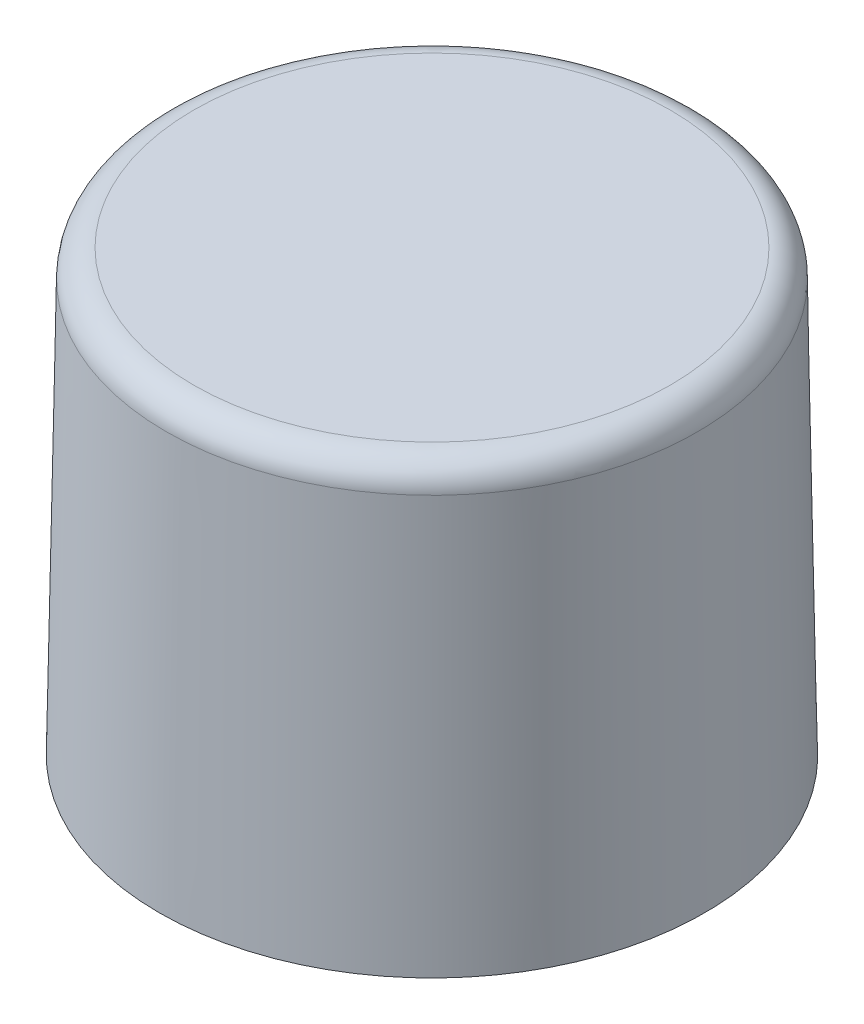
SolidWorks part; units mm, degrees
ref_plane "Front Plane" through (0, 0, 0) normal (0, 0, 1) x (1, 0, 0)
ref_plane "Top Plane" through (0, 0, 0) normal (0, 1, 0) x (1, 0, 0)
ref_plane "Right Plane" through (0, 0, 0) normal (1, 0, 0) x (0, 0, -1)
sketch "Sketch1" plane through (0, 0, 0) normal (0, 0, 1) x (1, 0, 0)
  line L0 (0, 0) -> (0, 4.03)
  line L1 (0, 4.03) -> (-2.4297, 4.03)
  line L2 (-2.4297, 4.03) -> (-2.5, 0)
  line L3 (-2.5, 0) -> (0, 0)
  line L4 (0, 0) -> (0, -1) construction
  line L5 (0, 2.6) -> (-1.8426, 2.6) construction
  line L6 (-2, 0) -> (-1.8845, 0.2)
  line L7 (-1.8845, 0.2) -> (-1.8278, 3.45)
  line L8 (-1.8278, 3.45) -> (0, 3.45)
  point P10 (0, 2.015)
  point P13 (0, -1.0864)
  point P14 (0, 0)
  point P15 (-2, 2.6)
  point P16 (-1.8426, 2.6)
  point P17 (0, 0)
  point P18 (0, 0)
  dimension "D1" = 89
  dimension "D2" = 5
  dimension "D3" = 4.03
  dimension "D5" = 2.6
  dimension "D6" = 1
  dimension "D7" = 4
  dimension "D8" = 0.2
  dimension "D9" = 60
  dimension "D10" = 3.45
revolve "Revolve1" add sketch "Sketch1" angle 360 about L0
sketch "Sketch2" plane through (0, 3.45, 0) normal (0, -1, 0) x (1, 0, 0)
  line L0 (-2, 0) -> (-1.5, 0) construction
  line L1 (-2, 0.25) -> (-1.5, 0.25)
  line L2 (-2, -0.25) -> (-1.5, -0.25)
  circle A0 centre (0, 0) radius 1.25 construction
  circle A1 centre (0, 0) radius 2 construction
  arc A2 (-2, 0.25) -> (-2, -0.25) centre (-2, 0) ccw
  arc A3 (-1.5, -0.25) -> (-1.5, 0.25) centre (-1.5, 0) ccw
  point P8 (-1.75, 0)
  point P13 (-1.25, 0)
  dimension "D1" = 2.5
  dimension "D2" = 0.25
extrude "Boss-Extrude1" add sketch "Sketch2" along normal up to vertex (3.25 mm away) up to point (-1.8845, 0.2, 0)
pattern_circular "CirPattern1" count 6 over 360 about axis through (0, 0, 0) along (0, 1, 0) of "Boss-Extrude1"
sketch "Sketch3" plane through (0, 3.45, 0) normal (0, -1, 0) x (1, 0, 0)
  line L0 (0, 0.65) -> (0, 2) construction
  line L1 (-0.25, 0.65) -> (-0.25, 2)
  line L2 (0.25, 0.65) -> (0.25, 2)
  circle A0 centre (0, 0) radius 2 construction
  arc A1 (-0.25, 0.65) -> (0.25, 0.65) centre (0, 0.65) ccw
  arc A2 (0.25, 2) -> (-0.25, 2) centre (0, 2) ccw
  circle A3 centre (0, 0) radius 2.5 construction
  arc A4 (-1.5, -0.25) -> (-1.5, 0.25) centre (-1.5, 0) ccw construction
  point P5 (0, 1.325)
  point P10 (0, 2.5)
  point P11 (0, 0.4)
  point P15 (0, 2.5)
  point P19 (0, 0.65)
  point P20 (0, 0)
  dimension "D1" = 2.1
extrude "Boss-Extrude2" add sketch "Sketch3" along normal up to vertex (0.85 mm away) up to point (0, 2.6, 0)
pattern_circular "CirPattern2" count 3 over 360 about axis through (0, 0, 0) along (0, 1, 0) of "Boss-Extrude2"
fillet "Fillet1" radius 0.25 1 edges at (0, 4.03, -2.4297)
